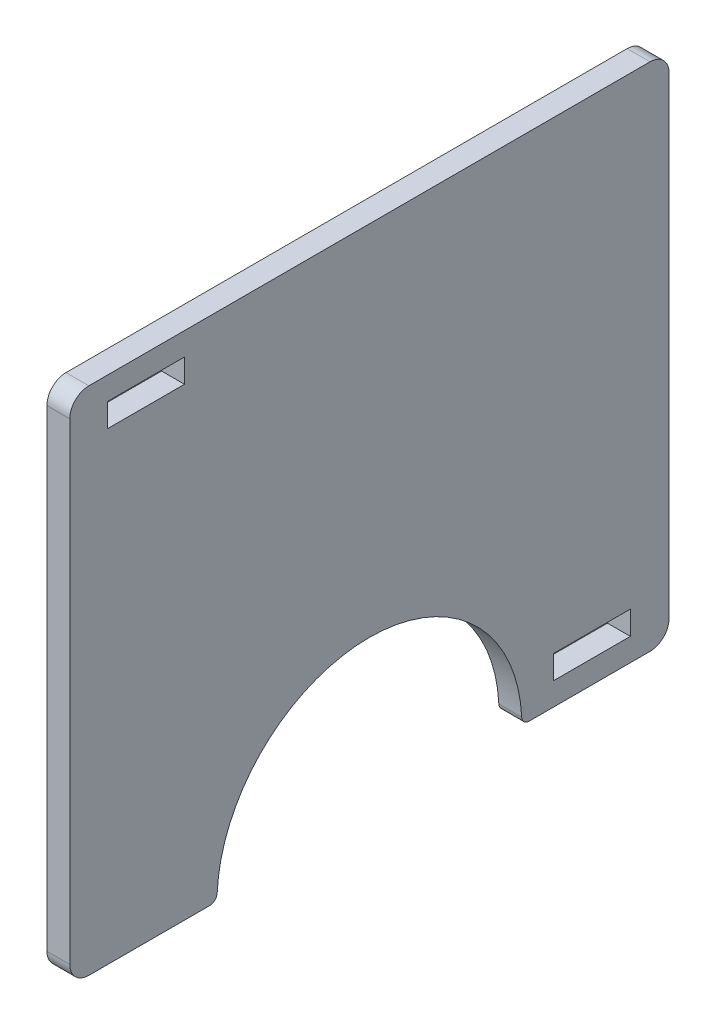
SolidWorks part; units mm, degrees
ref_plane "Alzado" through (0, 0, 0) normal (0, 0, 1) x (1, 0, 0)
ref_plane "Planta" through (0, 0, 0) normal (0, 1, 0) x (1, 0, 0)
ref_plane "Vista lateral" through (0, 0, 0) normal (1, 0, 0) x (0, 0, -1)
sketch "Croquis1" plane through (0, 0, 0) normal (1, 0, 0) x (0, 0, -1)
  line L1 (-36.82, 33.5) -> (36.82, 33.5)
  line L2 (-39.32, 31) -> (-39.32, -31)
  line L3 (-36.82, -33.5) -> (36.82, -33.5)
  line L4 (39.32, 31) -> (39.32, -31)
  line L5 (-39.32, 33.5) -> (39.32, -33.5) construction
  line L6 (-39.32, -33.5) -> (39.32, 33.5) construction
  arc A0 (-39.32, -31) -> (-36.82, -33.5) centre (-36.82, -31) ccw
  arc A1 (36.82, -33.5) -> (39.32, -31) centre (36.82, -31) ccw
  arc A2 (36.82, 33.5) -> (39.32, 31) centre (36.82, 31) cw
  arc A3 (-36.82, 33.5) -> (-39.32, 31) centre (-36.82, 31) ccw
  point P0 (0, 0)
  point P18 (-34.32, -33.5)
  dimension "D3" = 2.5
  dimension "D1" = 78.64
  dimension "D2" = 67
extrude "Saliente-Extruir1" add sketch "Croquis1" along normal blind 3
sketch "Croquis2" plane through (3, 0, 0) normal (1, 0, 0) x (0, 0, -1)
  line L0 (-36.82, -33.5) -> (36.82, -33.5) construction
  line L15 (0, 5.1674) -> (0, -3.1373) construction
  line L17 (-3.7832, 1.015) -> (6.0901, 1.015) construction
  line L18 (34.2349, -27.4) -> (24.1349, -27.4)
  line L19 (24.1349, -30.5) -> (24.1349, -27.4)
  line L20 (34.2349, -30.5) -> (24.1349, -30.5)
  line L21 (34.2349, -30.5) -> (34.2349, -27.4)
  line L22 (-34.37, 30.5) -> (-24.27, 30.5)
  line L23 (-24.27, 27.4) -> (-24.27, 30.5)
  line L24 (-34.37, 27.4) -> (-24.27, 27.4)
  line L25 (-34.37, 27.4) -> (-34.37, 30.5)
  circle A0 centre (0, -33.5) radius 20
  dimension "D1" = 40
extrude "Cortar-Extruir1" cut sketch "Croquis2" against normal mid plane 6
fillet "Redondeo1" radius 1 2 edges at (1.5, -33.5, -20) (1.5, -33.5, 20)
